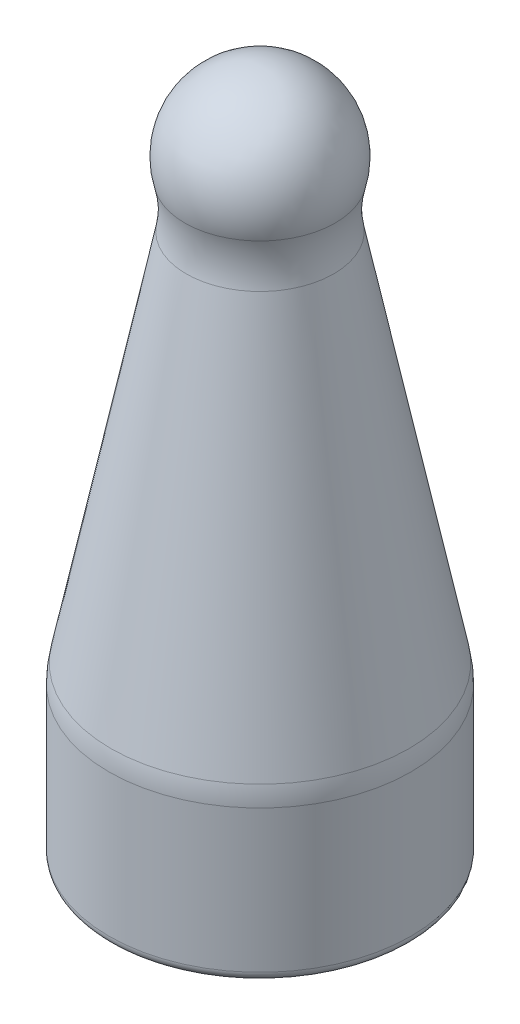
SolidWorks part; units mm, degrees
ref_plane "Plan de face" through (0, 0, 0) normal (0, 0, 1) x (1, 0, 0)
ref_plane "Plan de dessus" through (0, 0, 0) normal (0, 1, 0) x (1, 0, 0)
ref_plane "Plan de droite" through (0, 0, 0) normal (1, 0, 0) x (0, 0, -1)
sketch "Esquisse1" plane through (0, 0, 0) normal (0, 0, 1) x (1, 0, 0)
  line L1 (-12.5, 28.2) -> (-12.5, 31.5)
  line L2 (-15.5, 25.2) -> (-15.5, 0) construction
  line L5 (0, 95.8) -> (0, 37.8)
  line L7 (-12.5, 31.5) -> (-12.5, 28.2) construction
  line L8 (-12.5, 28.2) -> (-9.5, 28.2)
  line L9 (-9.5, 28.2) -> (-9.5, 25.2)
  line L10 (-9.5, 25.2) -> (-12.5, 25.2) construction
  line L11 (-15.5, 25.2) -> (-12.5, 25.2)
  line L12 (-12.5, 31.5) -> (-9.5, 31.5)
  line L13 (-9.5, 31.5) -> (-9.5, 34.5)
  line L14 (-9.5, 34.5) -> (-12.5, 34.5)
  line L15 (-12.5, 34.5) -> (-12.5, 37.8)
  line L17 (-15.5, 25.2) -> (-15.5, 41.8)
  line L18 (0, 95.8) -> (-0.4762, 95.8) construction
  line L19 (0, 37.8) -> (-12.5, 37.8)
  line L20 (0, 95.8) -> (0, 0) construction
  line L21 (-12.5, 25.2) -> (-9.5, 25.2)
  line L22 (-9.5, 25.2) -> (-9.5, 0) construction
  line L24 (-9.5, 0) -> (0, 0) construction
  line L28 (-1.9596, 83.2) -> (1.9596, 83.2) construction
  line L29 (-15.5, 41.8) -> (-7, 83.927)
  circle A1 centre (0, 87.8) radius 5 construction
  arc A2 (0, 95.8) -> (-7, 83.927) centre (0, 87.8) ccw
  point P32 (0, 92.8)
  dimension "D12" = 7
  dimension "D2" = 10
  dimension "D13" = 9.6
  dimension "D11" = 3
  dimension "D3" = 3.3
  dimension "D4" = 3
  dimension "D5" = 12.5
  dimension "D6" = 37.8
  dimension "D7" = 15.5
  dimension "D8" = 9.5
  dimension "D9" = 4
  dimension "D10" = 50
revolve "Révolution2" add sketch "Esquisse1" angle 360 about L5
fillet "Congé1" radius 10 2 edges at (-15.5, 41.8, 0) (-7, 83.927, 0)
fillet "Congé2" radius 1 1 edges at (-15.5, 25.2, 0)
